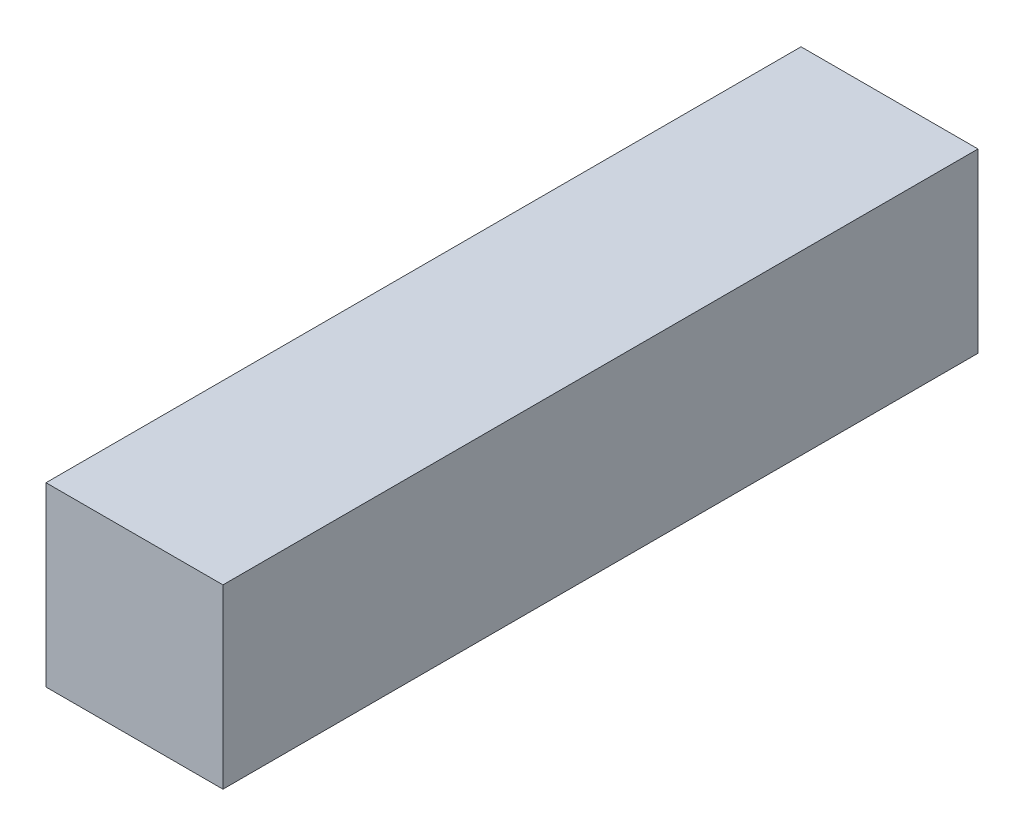
SolidWorks part; units mm, degrees
other "Imported1" parameters "D1"=113.1112, "Length"=113.1112, "Width"=2.3813, "D2"=51.1131, "Height"=2.3813
ref_plane "Front Plane" through (0, 0, 0) normal (0, 0, 1) x (1, 0, 0)
ref_plane "Top Plane" through (0, 0, 0) normal (0, 1, 0) x (1, 0, 0)
ref_plane "Right Plane" through (0, 0, 0) normal (1, 0, 0) x (0, 0, -1)
sketch "Sketch1" plane through (0, 0, 0) normal (0, 0, 1) x (1, 0, 0)
  line L0 (-1.1906, 1.1906) -> (1.1906, -1.1906) construction
  line L1 (-1.1906, 1.1906) -> (1.1906, 1.1906) construction
  line L2 (-1.1906, 1.1906) -> (-1.1906, -1.1906) construction
  line L3 (-1.1906, -1.1906) -> (1.1906, -1.1906) construction
  line L4 (1.1906, 1.1906) -> (1.1906, -1.1906) construction
sketch "Sketch2" plane through (0, 0, 0) normal (1, 0, 0) x (0, 0, -1)
  line L0 (152.4, 0) -> (-152.4, 0) construction
  line L1 (-152.4, 0) -> (-152.4, 1.1906) construction
  line L2 (-152.4, 1.1906) -> (152.4, 1.1906) construction
  line L3 (152.4, 1.1906) -> (152.4, 0) construction
  line L4 (-145.2562, 0) -> (-145.2562, 1.1906) construction
  line L5 (-145.2562, 0) -> (145.2562, 0) construction
  line L6 (145.2562, 0) -> (145.2562, 1.1906) construction
  point P2 (0, 1.1906)
  dimension "Length" = 304.8
  dimension "D1" = 7.1437
sketch "Sketch3" plane through (0, 0, 0) normal (0, 0, 1) x (1, 0, 0)
  line L0 (-1.1906, 1.1906) -> (1.1906, 1.1906)
  line L1 (1.1906, 1.1906) -> (1.1906, -1.1906)
  line L2 (1.1906, -1.1906) -> (-1.1906, -1.1906)
  line L3 (-1.1906, -1.1906) -> (-1.1906, 1.1906)
extrude "Boss-Extrude1" add sketch "Sketch3" along normal up to vertex (152.4 mm away) and the other way up to vertex (152.4 mm away) up to point (0, 0, 152.4) other way up to point (0, 0, -152.4)
ref_plane "Plane1" through (0, 0, 142.24) normal (0, 0, 1) x (1, 0, 0)
sketch "Sketch4" plane through (0, 0, 142.24) normal (0, 0, 1) x (1, 0, 0)
  circle A0 centre (0, 0) radius 8.1188
extrude "Cut-Extrude1" cut sketch "Sketch4" against normal through all
equation "\"D1@Sketch2\"=\"Height@Sketch1\"*3"
